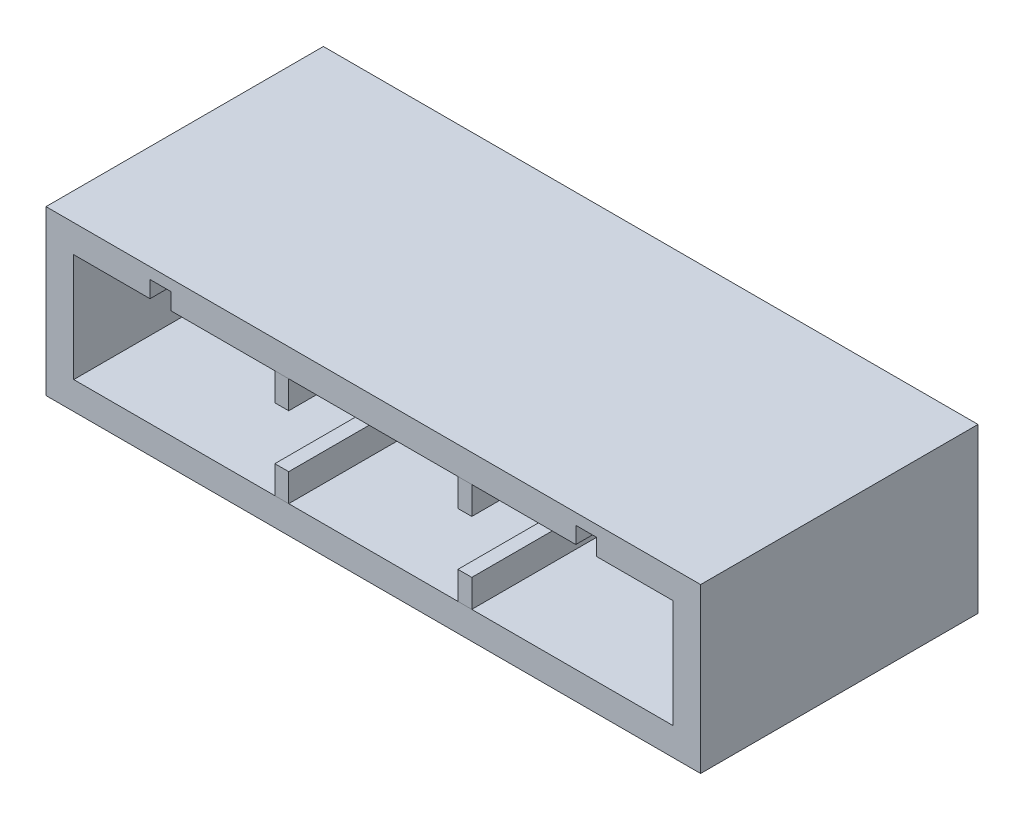
SolidWorks part; units mm, degrees
ref_plane "Alzado" through (0, 0, 0) normal (0, 0, 1) x (1, 0, 0)
ref_plane "Planta" through (0, 0, 0) normal (0, 1, 0) x (1, 0, 0)
ref_plane "Vista lateral" through (0, 0, 0) normal (1, 0, 0) x (0, 0, -1)
sketch "Croquis1" plane through (0, 0, 0) normal (0, 0, 1) x (1, 0, 0)
  line L0 (-21.6, -12.8603) -> (-21.6, -14.8603) construction
  line L1 (-21.6, -5.0603) -> (21.6, -5.0603)
  line L2 (-21.6, -5.0603) -> (-21.6, -12.8603)
  line L3 (-21.6, -12.8603) -> (21.6, -12.8603)
  line L4 (21.6, -5.0603) -> (21.6, -12.8603)
  line L5 (-21.6, -14.8603) -> (-23.6, -14.8603) construction
  line L7 (-23.6, -14.8603) -> (23.6, -14.8603)
  line L8 (-23.6, -14.8603) -> (-23.6, -3.0603)
  line L9 (-23.6, -3.0603) -> (23.6, -3.0603)
  line L10 (23.6, -14.8603) -> (23.6, -3.0603)
  point P5 (0, -5.0603)
  dimension "D1" = 43.2
  dimension "D2" = 7.8
  dimension "D3" = 2
  dimension "D4" = 2
  dimension "D5" = 47.2
  dimension "D6" = 11.8
extrude "Saliente-Extruir1" add sketch "Croquis1" along normal blind 20
sketch "Croquis2" plane through (0, 0, 20) normal (0, 0, 1) x (1, 0, 0)
  line L0 (-21.6, -5.0603) -> (-16.1, -5.0603) construction
  line L1 (21.6, -5.0603) -> (-21.6, -5.0603) construction
  line L2 (-16.1, -5.0603) -> (-16.1, -3.8603)
  line L3 (-16.1, -3.8603) -> (-14.6, -3.8603)
  line L4 (-14.6, -3.8603) -> (-14.6, -5.0603)
  line L5 (-14.6, -5.0603) -> (-16.1, -5.0603)
  line L6 (21.6, -5.0603) -> (16.1, -5.0603) construction
  line L7 (16.1, -5.0603) -> (16.1, -3.8603)
  line L8 (16.1, -3.8603) -> (14.6, -3.8603)
  line L9 (14.6, -3.8603) -> (14.6, -5.0603)
  line L10 (14.6, -5.0603) -> (16.1, -5.0603)
  dimension "D1" = 5.5
  dimension "D2" = 1.2
  dimension "D3" = 1.5
  dimension "D4" = 5.5
  dimension "D5" = 1.5
extrude "Cortar-Extruir1" cut sketch "Croquis2" against normal blind 20
sketch "Croquis3" plane through (0, 0, 20) normal (0, 0, 1) x (1, 0, 0)
  line L0 (-21.6, -5.0603) -> (-7.1, -5.0603) construction
  line L1 (14.6, -5.0603) -> (-14.6, -5.0603) construction
  line L2 (-7.1, -5.0603) -> (-7.1, -7.0603)
  line L3 (-7.1, -7.0603) -> (-6.1, -7.0603)
  line L4 (-6.1, -7.0603) -> (-6.1, -5.0603)
  line L5 (-6.1, -5.0603) -> (-7.1, -5.0603)
  line L6 (21.6, -5.0603) -> (7.1, -5.0603) construction
  line L7 (7.1, -5.0603) -> (7.1, -7.0603)
  line L8 (7.1, -7.0603) -> (6.1, -7.0603)
  line L9 (6.1, -7.0603) -> (6.1, -5.0603)
  line L10 (6.1, -5.0603) -> (7.1, -5.0603)
  line L11 (-7.1, -12.8603) -> (-7.1, -10.8603)
  line L12 (-21.6, -12.8603) -> (21.6, -12.8603) construction
  line L13 (-7.1, -10.8603) -> (-6.1, -10.8603)
  line L14 (-6.1, -10.8603) -> (-6.1, -12.8603)
  line L15 (-6.1, -12.8603) -> (-7.1, -12.8603)
  line L16 (6.1, -12.8603) -> (6.1, -10.8603)
  line L17 (6.1, -10.8603) -> (7.1, -10.8603)
  line L18 (7.1, -10.8603) -> (7.1, -12.8603)
  line L19 (7.1, -12.8603) -> (6.1, -12.8603)
  dimension "D1" = 14.5
  dimension "D2" = 2
  dimension "D3" = 1
  dimension "D4" = 14.5
  dimension "D5" = 1
  dimension "D6" = 2
extrude "Saliente-Extruir2" add sketch "Croquis3" against normal blind 20 separate body
